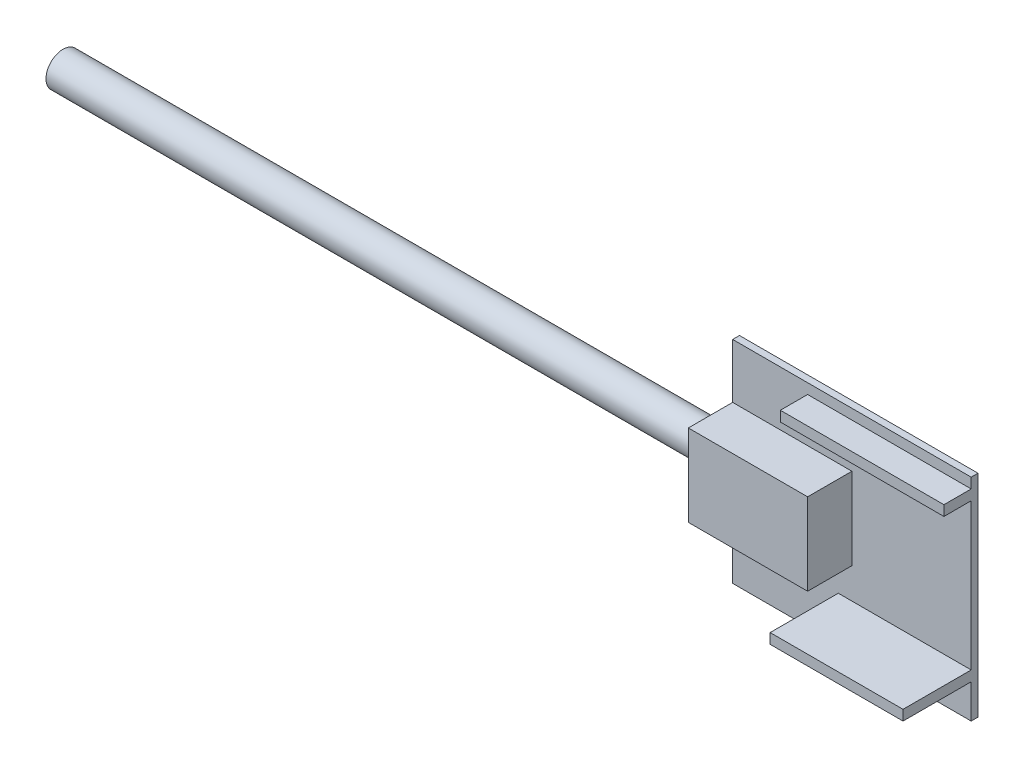
SolidWorks part; units mm, degrees
ref_plane "Plan de face" through (0, 0, 0) normal (0, 0, 1) x (1, 0, 0)
ref_plane "Plan de dessus" through (0, 0, 0) normal (0, 1, 0) x (1, 0, 0)
ref_plane "Plan de droite" through (0, 0, 0) normal (1, 0, 0) x (0, 0, -1)
sketch "Esquisse1" plane through (0, 0, 0) normal (0, 0, 1) x (1, 0, 0)
  line L1 (-35, 31) -> (35, 31)
  line L2 (-35, 31) -> (-35, -31)
  line L3 (-35, -31) -> (35, -31)
  line L4 (35, 31) -> (35, -31)
  dimension "D1" = 62
  dimension "D2" = 70
  dimension "D3" = 31
  dimension "D4" = 35
extrude "Boss.-Extru.1" add sketch "Esquisse1" along normal blind 2
sketch "Esquisse2" plane through (0, 0, 0) normal (0, 0, 1) x (1, 0, 0)
  line L0 (35, 31) -> (-35, 31) construction
  line L1 (-35, 15) -> (0, 15)
  line L2 (-35, 15) -> (-35, -9)
  line L3 (-35, -9) -> (0, -9)
  line L4 (0, 15) -> (0, -9)
  line L6 (-35, 31) -> (-35, -31) construction
  dimension "D1" = 24
  dimension "D2" = 16
  dimension "D3" = 0
  dimension "D4" = 35
extrude "Boss.-Extru.2" add sketch "Esquisse2" along normal blind 15
sketch "Esquisse3" plane through (0, 0, 0) normal (0, 0, 1) x (1, 0, 0)
  line L0 (35, -31) -> (35, 31) construction
  line L1 (-4, -18) -> (35, -18)
  line L2 (-4, -18) -> (-4, -21)
  line L3 (-4, -21) -> (35, -21)
  line L4 (35, -18) -> (35, -21)
  line L5 (-35, -31) -> (35, -31) construction
  point P8 (-4, -19.5)
  dimension "D1" = 3
  dimension "D2" = 0
  dimension "D3" = 10
  dimension "D4" = 39
extrude "Boss.-Extru.3" add sketch "Esquisse3" along normal blind 22
sketch "Esquisse4" plane through (0, 0, 0) normal (0, 0, 1) x (1, 0, 0)
  line L0 (35, -18) -> (35, 31) construction
  line L1 (-13, 28) -> (35, 28)
  line L2 (-13, 28) -> (-13, 25)
  line L3 (-13, 25) -> (35, 25)
  line L4 (35, 28) -> (35, 25)
  line L5 (35, 31) -> (-35, 31) construction
  dimension "D1" = 0
  dimension "D2" = 3
  dimension "D3" = 3
  dimension "D4" = 48
extrude "Boss.-Extru.4" add sketch "Esquisse4" along normal blind 10
sketch "Esquisse5" plane through (-35, 0, 0) normal (-1, 0, 0) x (0, 0, 1)
  line L0 (15, 15) -> (2, 15) construction
  line L1 (15, 15) -> (15, -9) construction
  circle A0 centre (8.5, 8) radius 5
  point P4 (8.5, 15)
  dimension "D3" = 10
  dimension "D1" = 7
  dimension "D2" = 6.5
extrude "Boss.-Extru.5" add sketch "Esquisse5" along normal blind 190
